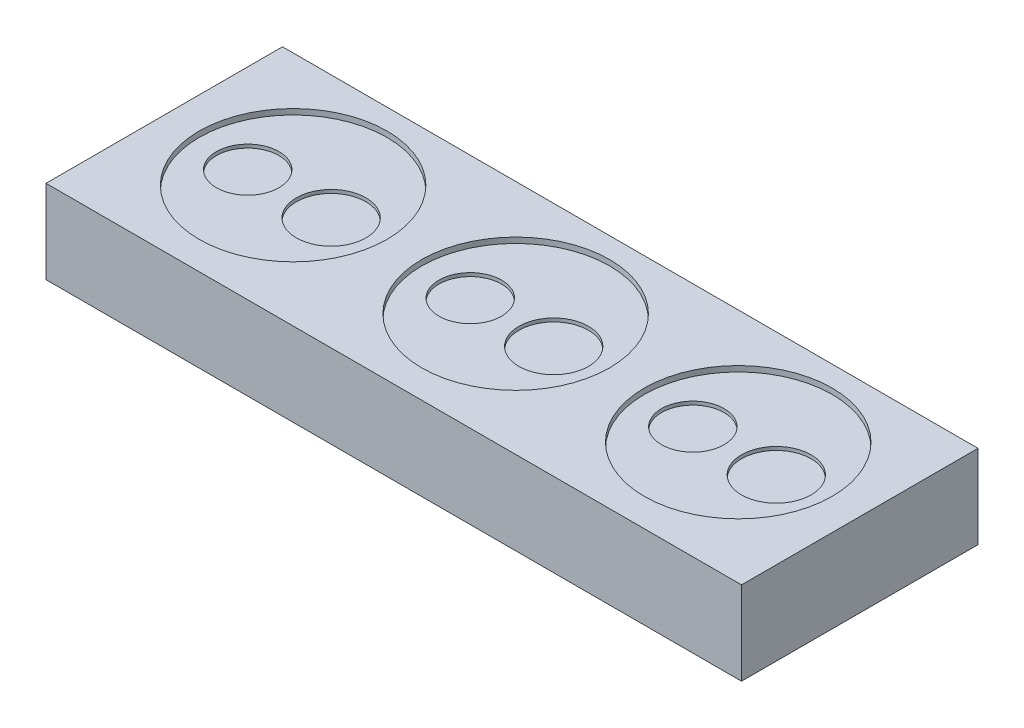
SolidWorks part; units mm, degrees
ref_plane "Front Plane" through (0, 0, 0) normal (0, 0, 1) x (1, 0, 0)
ref_plane "Top Plane" through (0, 0, 0) normal (0, 1, 0) x (1, 0, 0)
ref_plane "Right Plane" through (0, 0, 0) normal (1, 0, 0) x (0, 0, -1)
sketch "Sketch1" plane through (0, 0, 0) normal (0, 1, 0) x (1, 0, 0)
  line L1 (-255.5147, 108.4559) -> (244.4853, 108.4559)
  line L2 (-255.5147, 108.4559) -> (-255.5147, -61.5441)
  line L3 (-255.5147, -61.5441) -> (244.4853, -61.5441)
  line L4 (244.4853, 108.4559) -> (244.4853, -61.5441)
  dimension "D1" = 500
  dimension "D2" = 170
extrude "Boss-Extrude1" add sketch "Sketch1" along normal blind 60
sketch "Sketch3" plane through (0, 60, 0) normal (0, 1, 0) x (1, 0, 0)
  line L0 (244.4853, -61.5441) -> (244.4853, 108.4559) construction
  circle A0 centre (-5.5147, 26.0941) radius 67.5
  circle A1 centre (154.4853, 26.0941) radius 67.5
  circle A2 centre (-165.5147, 26.0941) radius 67.5
  dimension "D1" = 160
  dimension "D4" = 135
  dimension "D2" = 160
  dimension "D3" = 90
extrude "Cut-Extrude1" cut sketch "Sketch3" against normal blind 4
sketch "Sketch4" plane through (0, 56, 0) normal (0, 1, 0) x (1, 0, 0)
  line L0 (-255.5147, 23.4559) -> (298.9654, 23.4559) construction
  line L1 (-255.5147, 108.4559) -> (-255.5147, -61.5441) construction
  line L2 (-5.5147, 108.4559) -> (-5.5147, -137.9486) construction
  line L4 (244.4853, 108.4559) -> (-255.5147, 108.4559) construction
  line L5 (-165.5147, 93.5941) -> (-165.5147, -78.8733) construction
  circle A0 centre (-135.5147, 23.4559) radius 25
  circle A1 centre (-195.5147, 23.4559) radius 22.5
  circle A2 centre (-165.5147, 26.0941) radius 67.5 construction
  circle A3 centre (-35.5147, 23.4559) radius 22.5
  circle A4 centre (24.4853, 23.4559) radius 25
  circle A5 centre (124.4853, 23.4559) radius 22.5
  circle A6 centre (184.4853, 23.4559) radius 25
  dimension "D1" = 50
  dimension "D2" = 45
  dimension "D4" = 3
  dimension "D3" = 30
extrude "Cut-Extrude2" cut sketch "Sketch4" against normal blind 2.5
